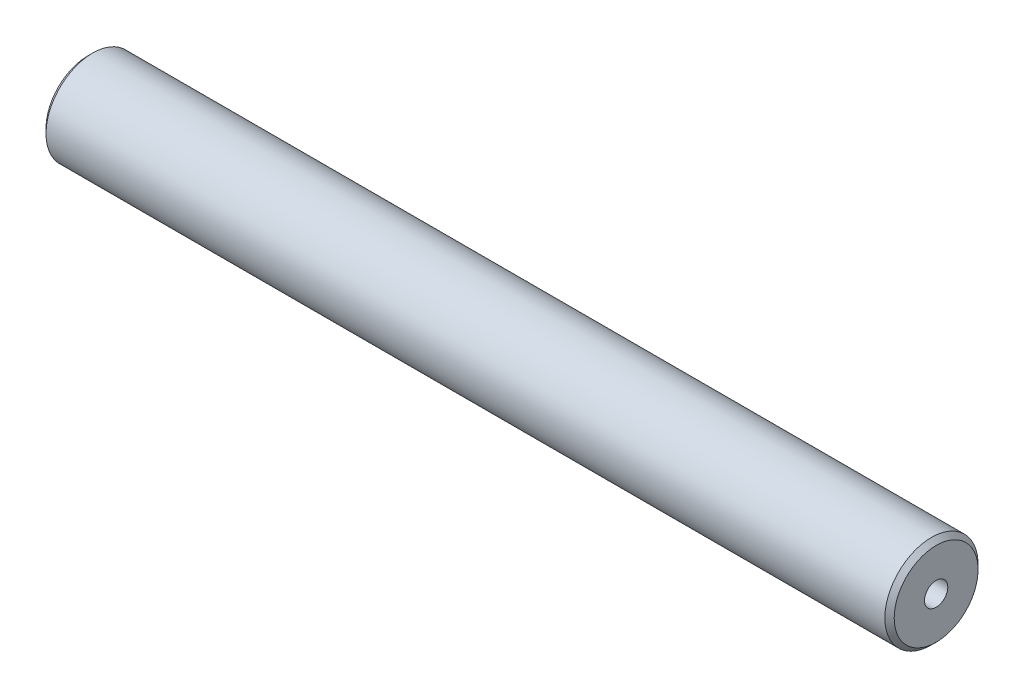
SolidWorks part; units mm, degrees
material "Liga 1060"
ref_plane "Plano frontal" through (0, 0, 0) normal (0, 0, 1) x (1, 0, 0)
ref_plane "Plano superior" through (0, 0, 0) normal (0, 1, 0) x (1, 0, 0)
ref_plane "Plano direito" through (0, 0, 0) normal (1, 0, 0) x (0, 0, -1)
sketch "Esboço1" plane through (0, 0, 0) normal (0, 0, 1) x (1, 0, 0)
  line L0 (0, 0) -> (182, 0)
  line L1 (0, 0) -> (182, 0) construction
  line L2 (0, 0) -> (0, 10)
  line L3 (0, 10) -> (182, 10)
  line L4 (182, 0) -> (182, 10)
  dimension "D1" = 20
  dimension "D2" = 182
revolve "Revolução1" add sketch "Esboço1" angle 360 about L1
chamfer "Chanfro1" distance 1 angle 45 2 edges at (182, 0, 10) (0, 0, 10)
hole_wizard "Furo roscado de M61" positions "Esboço3" profile "Esboço2" tap size "M6" standard "DIN"
sketch "Esboço3" plane through (182, 0, 0) normal (1, 0, 0) x (0, 0, -1)
  point P0 (0, 0)
sketch "Esboço2" plane through (182, 0, 0) normal (0, 1, 0) x (0, 0, -1)
  line L0 (0, 0) -> (0, 18.5022)
  line L1 (0, 18.5022) -> (2.5, 17)
  line L2 (2.5, 17) -> (2.5, 0)
  line L5 (2.5, 0) -> (0, 0)
  line L10 (0, 18.5022) -> (-2.5, 17) construction
  line L11 (0, -6.35) -> (0, 107.95) construction
  dimension "Tap Drill Dia." = 5
  dimension "Tap Drill Depth" = 17
  dimension "Drill Angle" = 118
cosmetic thread "Rosca de furo1" parameters "D1"=12, "D2"=6
hole_wizard "Furo roscado de M62" positions "Esboço5" profile "Esboço4" tap size "M6" standard "DIN"
sketch "Esboço5" plane through (0, 0, 0) normal (-1, 0, 0) x (0, 0, 1)
  point P0 (0, 0)
sketch "Esboço4" plane through (0, 0, 0) normal (0, 1, 0) x (0, 0, 1)
  line L0 (0, 0) -> (0, 18.5022)
  line L1 (0, 18.5022) -> (2.5, 17)
  line L2 (2.5, 17) -> (2.5, 0)
  line L5 (2.5, 0) -> (0, 0)
  line L10 (0, 18.5022) -> (-2.5, 17) construction
  line L11 (0, -6.35) -> (0, 107.95) construction
  dimension "Tap Drill Dia." = 5
  dimension "Tap Drill Depth" = 17
  dimension "Drill Angle" = 118
cosmetic thread "Rosca de furo2" parameters "D1"=12, "D2"=6
ref_plane "Plano1" through (91, 0, 0) normal (1, 0, 0) x (0, 0, -1)
